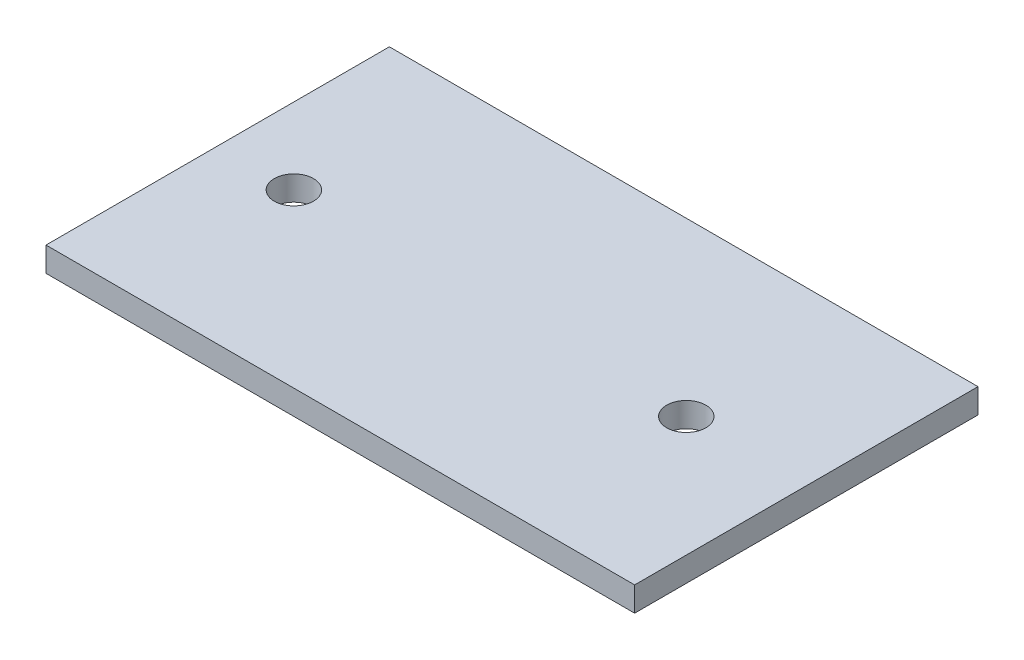
SolidWorks part; units mm, degrees
ref_plane "Front Plane" through (0, 0, 0) normal (0, 0, 1) x (1, 0, 0)
ref_plane "Top Plane" through (0, 0, 0) normal (0, 1, 0) x (1, 0, 0)
ref_plane "Right Plane" through (0, 0, 0) normal (1, 0, 0) x (0, 0, -1)
sketch "Sketch1" plane through (0, 0, 0) normal (0, 1, 0) x (1, 0, 0)
  line L0 (-15.5286, -30.0341) -> (104.4714, -30.0341) construction
  line L1 (-15.5286, 4.9659) -> (104.4714, 4.9659)
  line L2 (-15.5286, 4.9659) -> (-15.5286, -65.0341)
  line L3 (-15.5286, -65.0341) -> (104.4714, -65.0341)
  line L4 (104.4714, 4.9659) -> (104.4714, -65.0341)
  circle A0 centre (0, -30.0341) radius 4
  circle A1 centre (80, -30.0341) radius 4
  dimension "D3" = 8
  dimension "D4" = 8
  dimension "D1" = 70
  dimension "D2" = 120
  dimension "D5" = 80
extrude "Boss-Extrude1" add sketch "Sketch1" along normal blind 5
